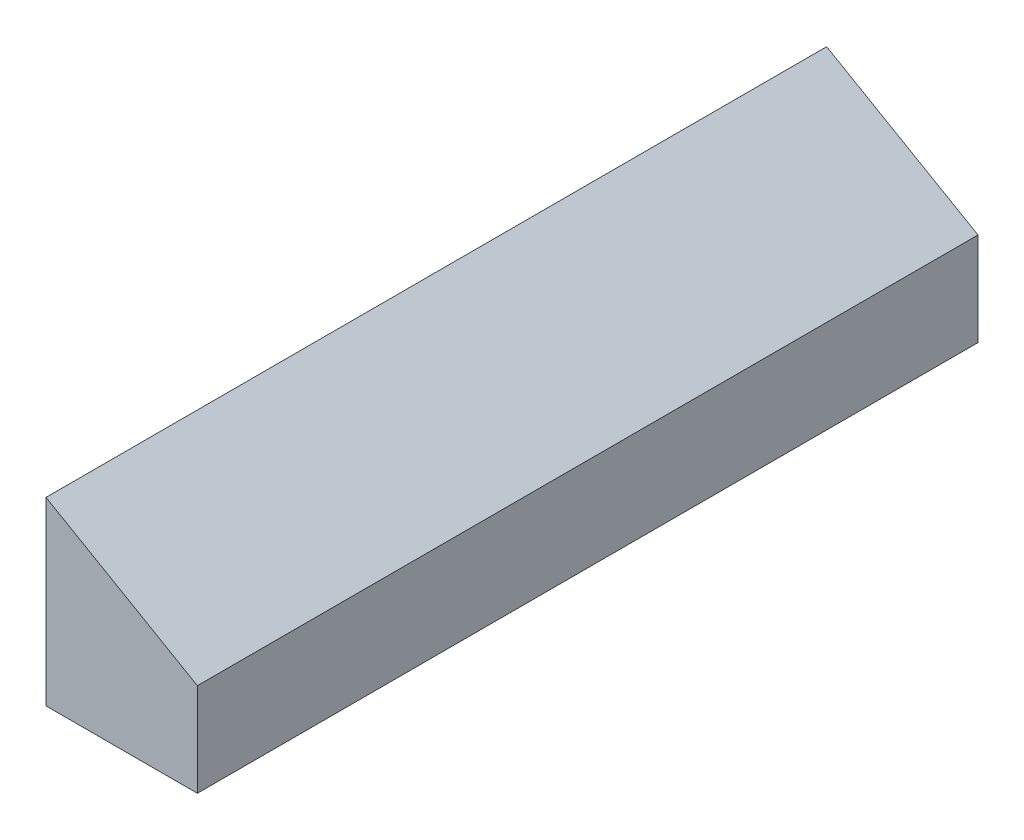
SolidWorks part; units mm, degrees
ref_plane "Front Plane" through (0, 0, 0) normal (0, 0, 1) x (1, 0, 0)
ref_plane "Top Plane" through (0, 0, 0) normal (0, 1, 0) x (1, 0, 0)
ref_plane "Right Plane" through (0, 0, 0) normal (1, 0, 0) x (0, 0, -1)
sketch "Sketch1" plane through (0, 0, 0) normal (0, 0, 1) x (1, 0, 0)
  line L12 (0, 0) -> (-50000, 0) construction
  line L13 (0, 0) -> (0, 15.5)
  line L14 (0, 15.5) -> (12.9904, 8)
  line L15 (0, 0) -> (12.9904, 0)
  line L16 (12.9904, 0) -> (12.9904, 8)
  dimension "D1" = 8
  dimension "D2" = 30
  dimension "D3" = 15
extrude "Boss-Extrude1" add sketch "Sketch1" along normal blind 67
